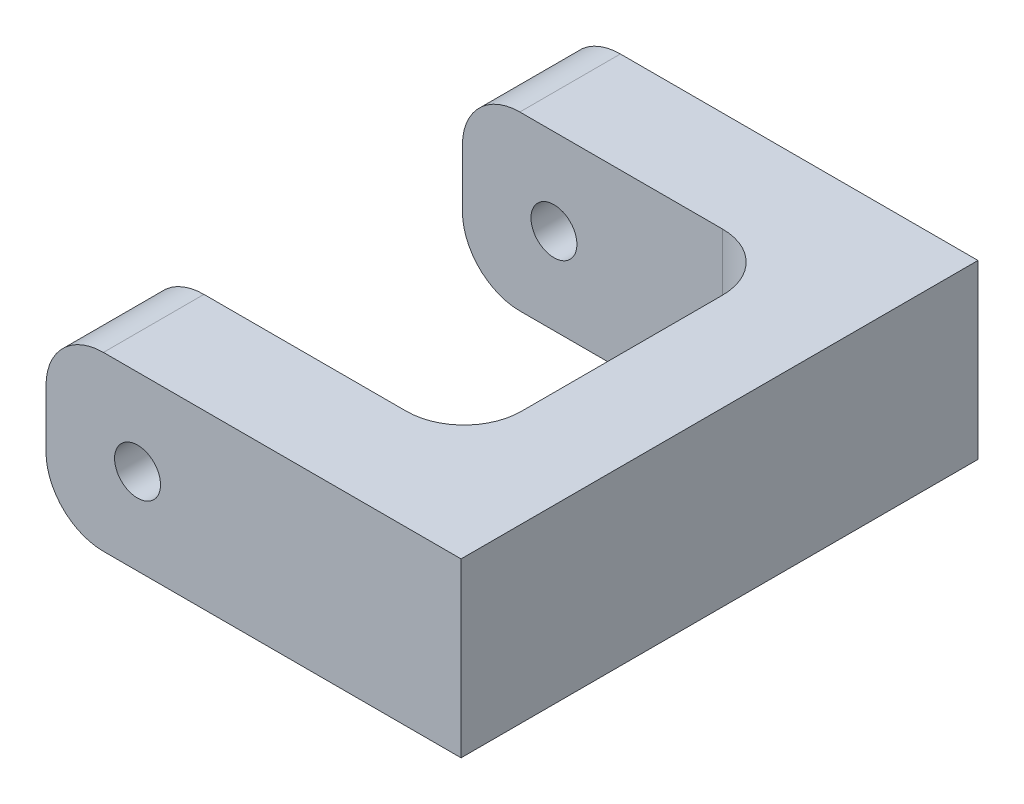
SolidWorks part; units mm, degrees
ref_plane "Спереди" through (0, 0, 0) normal (0, 0, 1) x (1, 0, 0)
ref_plane "Сверху" through (0, 0, 0) normal (0, 1, 0) x (1, 0, 0)
ref_plane "Справа" through (0, 0, 0) normal (1, 0, 0) x (0, 0, -1)
sketch "Эскиз1" plane through (0, 0, 0) normal (0, 0, 1) x (1, 0, 0)
  line L0 (-0.1149, -4.0419) -> (-0.1149, -14.0419)
  line L3 (9.8851, -24.0419) -> (72.1527, -24.0419)
  line L4 (9.8851, 5.9581) -> (72.1527, 5.9581)
  line L5 (72.1527, 5.9581) -> (72.1527, -24.0419)
  line L6 (15.824, -9.0419) -> (68.2142, -9.0419) construction
  arc A1 (-0.1149, -4.0419) -> (9.8851, 5.9581) centre (9.8851, -4.0419) cw
  arc A2 (-0.1149, -14.0419) -> (9.8851, -24.0419) centre (9.8851, -14.0419) ccw
  point P15 (-0.1149, 5.9581)
  point P18 (-0.1149, -24.0419)
  dimension "D4" = 10
  dimension "D2" = 15
  dimension "D3" = 15
extrude "Вытянуть1" add sketch "Эскиз1" against normal blind 90 from offset 19
sketch "Эскиз3" plane through (0, 0, 0) normal (0, 1, 0) x (1, 0, 0)
  line L0 (-2.2661, 53.5) -> (55.1527, 53.5)
  line L1 (55.1527, 53.5) -> (55.1527, -1.5)
  line L2 (55.1527, -1.5) -> (-2.2661, -1.5)
  line L4 (-2.2661, -1.5) -> (-2.2661, 53.5)
  line L5 (72.1527, 71) -> (72.1527, -19) construction
  line L8 (72.1527, 71) -> (9.8851, 71) construction
  line L9 (72.1527, -19) -> (9.8851, -19) construction
  dimension "D1" = 17
  dimension "D2" = 17.5
  dimension "D3" = 17.5
extrude "Вырез-Вытянуть1" cut sketch "Эскиз3" against normal mid plane 87
sketch "Эскиз4" plane through (0, 0, 0) normal (0, 0, 1) x (1, 0, 0)
  circle A0 centre (15.824, -9.0419) radius 4
  dimension "D1" = 8
extrude "Вырез-Вытянуть2" cut sketch "Эскиз4" against normal mid plane 200
fillet "Скругление1" radius 10 2 edges at (55.1527, -9.0419, 1.5) (55.1527, -9.0419, -53.5)
